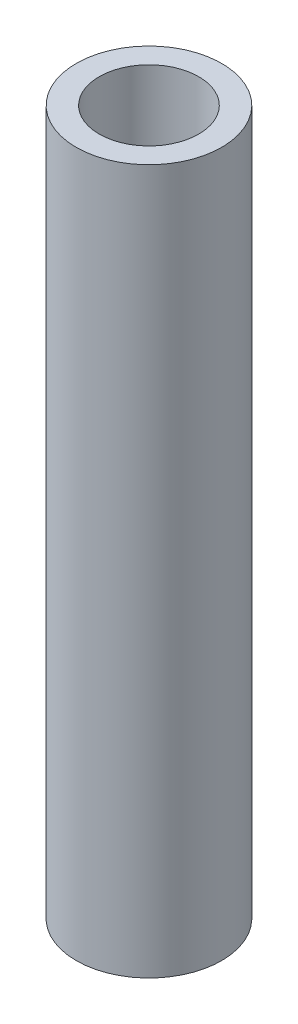
SolidWorks part; units mm, degrees
ref_plane "Front Plane" through (0, 0, 0) normal (0, 0, 1) x (1, 0, 0)
ref_plane "Top Plane" through (0, 0, 0) normal (0, 1, 0) x (1, 0, 0)
ref_plane "Right Plane" through (0, 0, 0) normal (1, 0, 0) x (0, 0, -1)
sketch "Sketch1" plane through (0, 0, 0) normal (0, 1, 0) x (1, 0, 0)
  circle A0 centre (0, 0) radius 3.25
  circle A1 centre (0, 0) radius 4.75
  dimension "D1" = 6.5
  dimension "D2" = 1.5
extrude "Boss-Extrude1" add sketch "Sketch1" along normal blind 46
